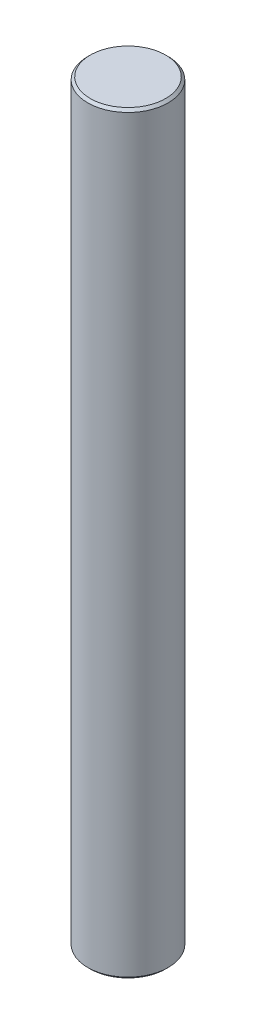
SolidWorks part; units mm, degrees
material "AISI 304"
ref_plane "Front Plane" through (0, 0, 0) normal (0, 0, 1) x (1, 0, 0)
ref_plane "Top Plane" through (0, 0, 0) normal (0, 1, 0) x (1, 0, 0)
ref_plane "Right Plane" through (0, 0, 0) normal (1, 0, 0) x (0, 0, -1)
sketch "Sketch1" plane through (0, 0, 0) normal (0, 1, 0) x (1, 0, 0)
  circle A0 centre (0, 0) radius 4
  dimension "D1" = 8
extrude "Boss-Extrude1" add sketch "Sketch1" along normal blind 75
chamfer "Chamfer1" distance 0.25 angle 45 2 edges at (0, 0, 4) (0, 75, 4)
